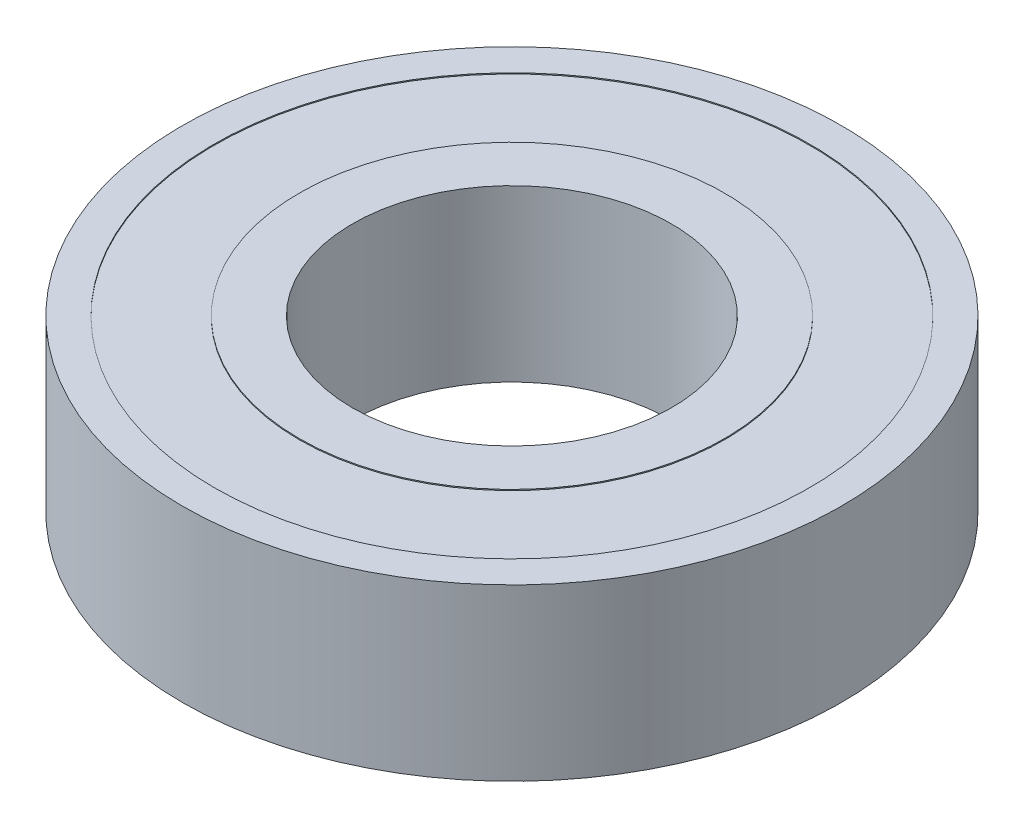
SolidWorks part; units mm, degrees
ref_plane "前视基准面" through (0, 0, 0) normal (0, 0, 1) x (1, 0, 0)
ref_plane "上视基准面" through (0, 0, 0) normal (0, 1, 0) x (1, 0, 0)
ref_plane "右视基准面" through (0, 0, 0) normal (1, 0, 0) x (0, 0, -1)
other "Configuration Table"
sketch "Sketch1" plane through (0, 0, 0) normal (0, 1, 0) x (1, 0, 0)
  circle A0 centre (0, 0) radius 31
  circle A1 centre (0, 0) radius 15
extrude "Boss-Extrude2" add sketch "Sketch1" along normal blind 8
sketch "Sketch4" plane through (0, 8, 0) normal (0, 1, 0) x (1, 0, 0)
  circle A0 centre (0, 0) radius 20
  circle A1 centre (0, 0) radius 28
extrude "Cut-Extrude2" cut sketch "Sketch4" against normal blind 0.1
mirror "Mirror2" of "Boss-Extrude2", "Cut-Extrude2"
